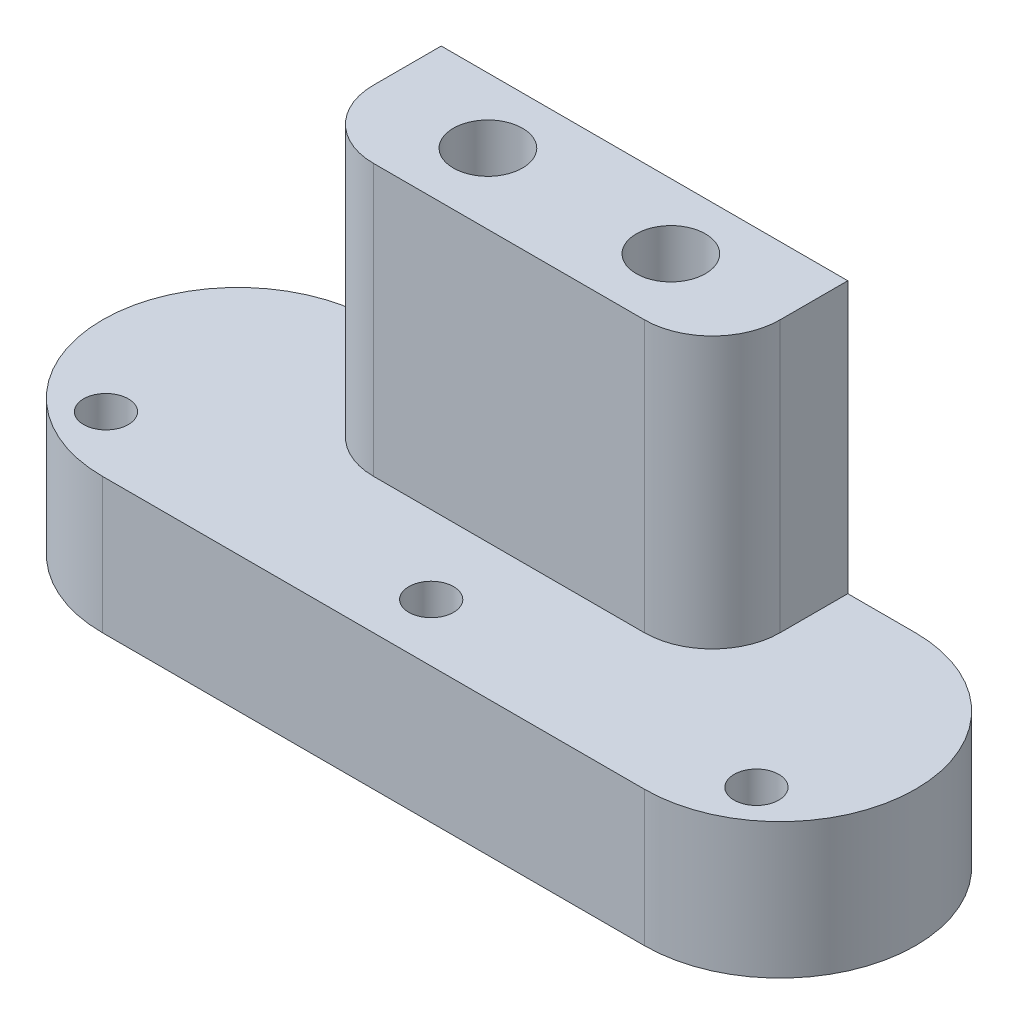
SolidWorks part; units mm, degrees
ref_plane "Front Plane" through (0, 0, 0) normal (0, 0, 1) x (1, 0, 0)
ref_plane "Top Plane" through (0, 0, 0) normal (0, 1, 0) x (1, 0, 0)
ref_plane "Right Plane" through (0, 0, 0) normal (1, 0, 0) x (0, 0, -1)
sketch "Sketch3" plane through (0, 0, 0) normal (0, 1, 0) x (1, 0, 0)
  line L0 (-20, 0) -> (20, 0) construction
  line L1 (-20, 10) -> (20, 10)
  line L2 (-20, -10) -> (20, -10)
  arc A0 (-20, 10) -> (-20, -10) centre (-20, 0) ccw
  arc A1 (20, -10) -> (20, 10) centre (20, 0) ccw
  point P3 (0, 0)
  dimension "D1" = 10
  dimension "D2" = 40
  dimension "D3" = 20
extrude "Boss-Extrude1" add sketch "Sketch3" along normal blind 10
hole_wizard "Tap Drill for M4x0.7 Tap1" positions "Sketch4" profile "Sketch5" hole size "M4x0.7" standard "ANSI Metric" end condition up to next
sketch "Sketch4" plane through (0, 10, 0) normal (0, 1, 0) x (1, 0, 0)
  point P11 (0, -5.7412)
  point P13 (24, -5.7412)
  point P15 (-24, -5.7412)
  point P18 (0, 0)
  point P19 (0, 0)
sketch "Sketch5" plane through (0, 10, 5.7412) normal (1, 0, 0) x (0, 0, 1)
  line L0 (0, 0) -> (0, 10)
  line L1 (0, 10) -> (1.65, 10)
  line L2 (1.65, 10) -> (1.65, 0)
  line L5 (1.65, 0) -> (0, 0)
  line L11 (0, -6.35) -> (0, 107.95) construction
  dimension "Thru Hole Dia." = 3.3
  dimension "Thru Hole Depth" = 10
sketch "Sketch8" plane through (0, 10, 0) normal (0, 1, 0) x (1, 0, 0)
  line L0 (20, 10) -> (-20, 10) construction
  line L1 (-15, 0) -> (15, 0)
  line L2 (-15, 0) -> (-15, 10)
  line L3 (-15, 10) -> (15, 10)
  line L4 (15, 0) -> (15, 10)
  line L5 (-20, -10) -> (20, -10) construction
  dimension "D1" = 0
  dimension "D2" = 10
  dimension "D3" = 15
  dimension "D4" = 15
extrude "Boss-Extrude2" add sketch "Sketch8" along normal blind 20 contours L3 L4 L1 L2
fillet "Fillet1" radius 5 2 edges at (-15, 20, 0) (15, 20, 0)
hole_wizard "Ø1.0mm Dowel Hole1" positions "Sketch9" profile "Sketch10" hole size "Ø1.0" standard "ANSI Metric"
sketch "Sketch9" plane through (0, 30, 0) normal (0, 1, 0) x (1, 0, 0)
  point P0 (-6.75, 5.1944)
  point P2 (6.75, 5.1944)
  point P6 (6.75, 3.554)
  point P7 (6.75, 7.2448)
  point P8 (0, 0)
  point P9 (6.75, 5.1944)
  dimension "D1" = 6.75
  dimension "D2" = 6.75
sketch "Sketch10" plane through (-6.75, 30, -5.1944) normal (1, 0, 0) x (0, 0, 1)
  line L0 (0, 0) -> (0, 6.35)
  line L1 (0, 6.35) -> (2.55, 3.8)
  line L2 (2.55, 3.8) -> (2.55, 0)
  line L5 (2.55, 0) -> (0, 0)
  line L10 (0, 6.35) -> (-2.55, 3.8) construction
  line L11 (0, -6.35) -> (0, 107.95) construction
  dimension "Hole Dia." = 5.1
  dimension "Hole Depth" = 3.8
  dimension "Drill Angle" = 90
